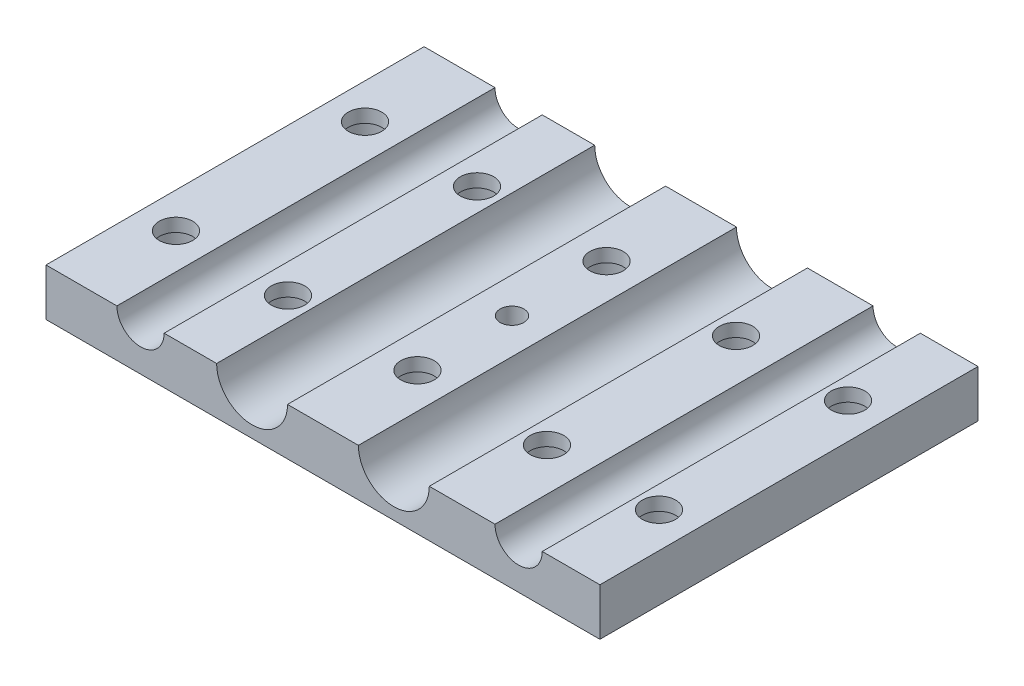
SolidWorks part; units mm, degrees
material "Copper"
ref_plane "Front Plane" through (0, 0, 0) normal (0, 0, 1) x (1, 0, 0)
ref_plane "Top Plane" through (0, 0, 0) normal (0, 1, 0) x (1, 0, 0)
ref_plane "Right Plane" through (0, 0, 0) normal (1, 0, 0) x (0, 0, -1)
sketch "Sketch1" plane through (0, 0, 0) normal (0, 1, 0) x (1, 0, 0)
  line L1 (-37.211, 25.4) -> (37.211, 25.4)
  line L2 (-37.211, 25.4) -> (-37.211, -25.4)
  line L3 (-37.211, -25.4) -> (37.211, -25.4)
  line L4 (37.211, 25.4) -> (37.211, -25.4)
  dimension "D1" = 50.8
  dimension "D2" = 74.422
  dimension "D3" = 37.211
  dimension "D4" = 25.4
extrude "Boss-Extrude1" add sketch "Sketch1" along normal blind 6.35
sketch "Sketch2" plane through (0, 0, 25.4) normal (0, 0, 1) x (1, 0, 0)
  line L0 (-37.211, 0) -> (37.211, 0) construction
  line L1 (-37.211, 6.35) -> (-37.211, 0) construction
  circle A0 centre (-24.511, 0) radius 3.175
  circle A1 centre (26.289, 0) radius 3.175
  dimension "D3" = 6.35
  dimension "D1" = 50.8
  dimension "D2" = 12.7
extrude "Cut-Extrude1" cut sketch "Sketch2" against normal through all
sketch "Sketch3" plane through (0, 0, 25.4) normal (0, 0, 1) x (1, 0, 0)
  line L0 (-21.336, 0) -> (23.114, 0) construction
  circle A0 centre (-9.525, 0) radius 4.7625
  circle A1 centre (9.525, 0) radius 4.7625
  dimension "D1" = 9.525
  dimension "D2" = 19.05
  dimension "D3" = 9.525
extrude "Cut-Extrude2" cut sketch "Sketch3" against normal through all
hole_wizard "#8 Clearance Hole1" positions "Sketch5" profile "Sketch4" hole size "#8" standard "ANSI Inch" end condition through all
sketch "Sketch5" plane through (0, 6.35, 0) normal (0, 1, 0) x (1, 0, 0)
  line L2 (37.211, 25.4) -> (-37.211, 25.4) construction
  line L3 (-37.211, -25.4) -> (37.211, -25.4) construction
  line L4 (-37.211, 25.4) -> (-37.211, -25.4) construction
  line L5 (37.211, -25.4) -> (37.211, 25.4) construction
  point P0 (-32.4485, 12.7)
  point P2 (-32.4485, -12.7)
  point P4 (-17.399, -12.7)
  point P6 (0, -12.7)
  point P8 (17.399, -12.7)
  point P10 (32.4485, -12.7)
  point P12 (32.4485, 12.7)
  point P14 (17.399, 12.7)
  point P16 (0, 12.7)
  point P18 (-17.399, 12.7)
  dimension "D1" = 12.7
  dimension "D2" = 12.7
  dimension "D3" = 4.7625
  dimension "D4" = 4.7625
  dimension "D5" = 19.812
  dimension "D6" = 19.812
sketch "Sketch4" plane through (-32.4485, 6.35, -12.7) normal (1, 0, 0) x (0, 0, 1)
  line L0 (0, 0) -> (0, 6.35)
  line L1 (0, 6.35) -> (2.2479, 6.35)
  line L2 (2.2479, 6.35) -> (2.2479, 0)
  line L5 (2.2479, 0) -> (0, 0)
  line L11 (0, -6.35) -> (0, 107.95) construction
  dimension "Thru Hole Dia." = 4.4958
  dimension "Thru Hole Depth" = 6.35
sketch "Sketch6" plane through (0, 6.35, 0) normal (0, 1, 0) x (1, 0, 0)
  circle A0 centre (-32.4485, 12.7) radius 3.429
  circle A1 centre (-17.399, 12.7) radius 3.429
  circle A2 centre (0, 12.7) radius 3.429
  circle A3 centre (17.399, 12.7) radius 3.429
  circle A4 centre (32.4485, 12.7) radius 3.429
  circle A5 centre (32.4485, -12.7) radius 3.429
  circle A6 centre (17.399, -12.7) radius 3.429
  circle A7 centre (0, -12.7) radius 3.429
  circle A8 centre (-17.399, -12.7) radius 3.429
  circle A9 centre (-32.4485, -12.7) radius 3.429
  dimension "D1" = 6.858
extrude "Cut-Extrude3" cut sketch "Sketch6" against normal blind 4.572
sketch "Sketch7" plane through (0, 6.35, 0) normal (0, 1, 0) x (1, 0, 0)
  circle A0 centre (0, 0) radius 1.5875
  dimension "D1" = 3.175
extrude "Cut-Extrude4" cut sketch "Sketch7" against normal through all
move or copy body "Body-Move/Copy3" bodies to move or copy 110 copy no rotation origin (0, 3.175, 0) rotation axis (1, 0, 0) rotation angle 180
